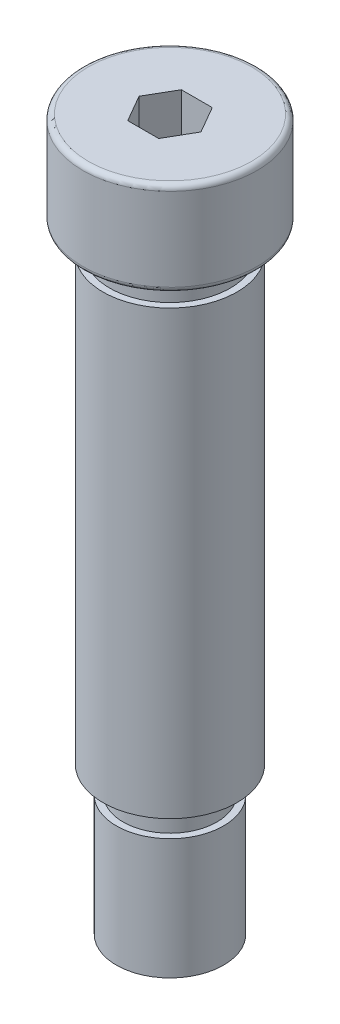
SolidWorks part; units mm, degrees
material "AISI 304"
ref_plane "前视基准面" through (0, 0, 0) normal (0, 0, 1) x (1, 0, 0)
ref_plane "上视基准面" through (0, 0, 0) normal (0, 1, 0) x (1, 0, 0)
ref_plane "右视基准面" through (0, 0, 0) normal (1, 0, 0) x (0, 0, -1)
sketch "草图1" plane through (0, 0, 0) normal (0, 0, 1) x (1, 0, 0)
  line L0 (0, 0) -> (0, 53) construction
  line L1 (0, 53) -> (-6.1, 53)
  line L2 (-6.5, 52.6) -> (-6.5, 46.4)
  line L3 (-6.1, 46) -> (-4.5, 46)
  line L4 (-4.5, 46) -> (-4.5, 44)
  line L5 (-4.5, 44) -> (-5, 44)
  line L6 (-5, 44) -> (-5, 11)
  line L7 (-5, 11) -> (-3.5, 11)
  line L8 (-3.5, 11) -> (-3.5, 9)
  line L9 (-3.5, 9) -> (-4, 9)
  line L10 (-4, 9) -> (-4, 0)
  line L11 (-4, 0) -> (0, 0)
  line L12 (0, 0) -> (0, 53)
  arc A0 (-6.5, 46.4) -> (-6.1, 46) centre (-6.1, 46.4) ccw
  arc A1 (-6.1, 53) -> (-6.5, 52.6) centre (-6.1, 52.6) ccw
  point P17 (-6.5, 46)
  point P20 (-6.5, 53)
  dimension "D11" = 0.4
  dimension "D1" = 7
  dimension "D2" = 13
  dimension "D3" = 10
  dimension "D4" = 2
  dimension "D5" = 0.5
  dimension "D6" = 11
  dimension "D7" = 8
  dimension "D8" = 7
  dimension "D9" = 2
  dimension "D10" = 35
revolve "旋转1" add sketch "草图1" angle 360 about L0
cosmetic thread "装饰螺纹线1"
sketch "草图2" plane through (0, 53, 0) normal (0, 1, 0) x (1, 0, 0)
  line L1 (1.1547, 2) -> (-1.1547, 2)
  line L2 (-1.1547, 2) -> (-2.3094, 0)
  line L3 (-2.3094, 0) -> (-1.1547, -2)
  line L4 (-1.1547, -2) -> (1.1547, -2)
  line L5 (1.1547, -2) -> (2.3094, 0)
  line L6 (2.3094, 0) -> (1.1547, 2)
  circle A0 centre (0, 0) radius 2 construction
  dimension "D1" = 4
extrude "切除-拉伸1" cut sketch "草图2" against normal blind 3.5
